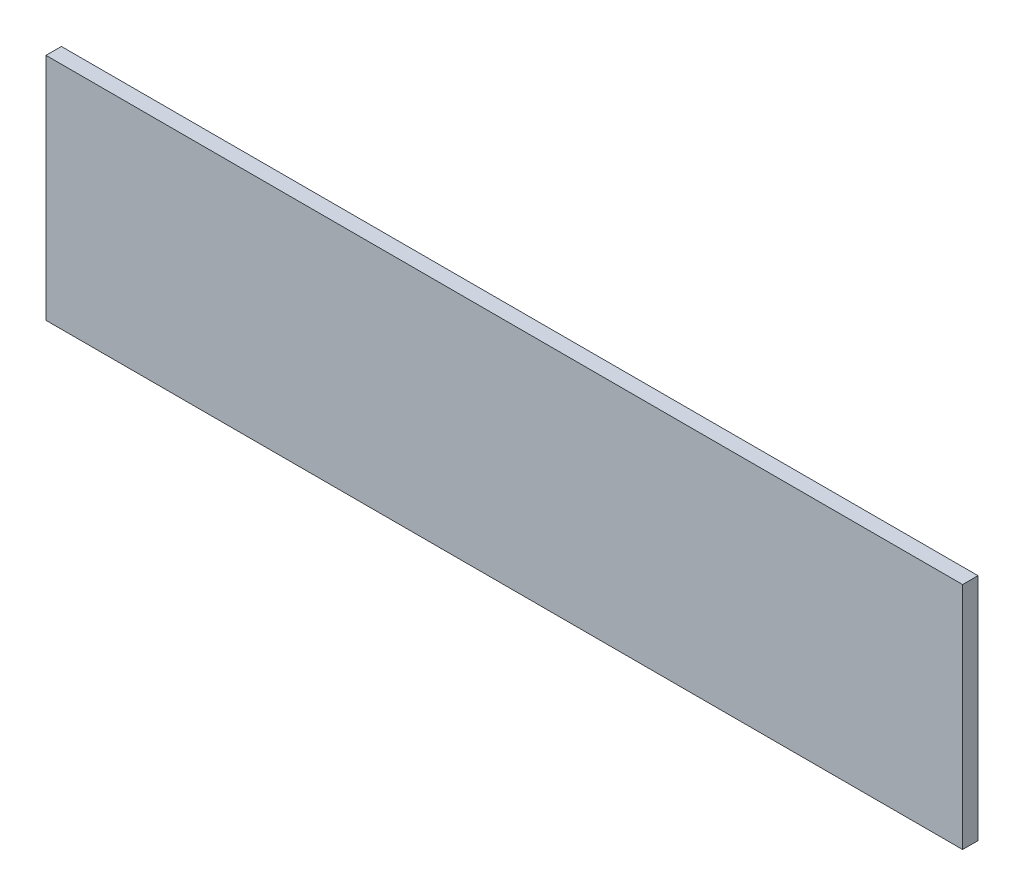
SolidWorks part; units mm, degrees
ref_plane "Front Plane" through (0, 0, 0) normal (0, 0, 1) x (1, 0, 0)
ref_plane "Top Plane" through (0, 0, 0) normal (0, 1, 0) x (1, 0, 0)
ref_plane "Right Plane" through (0, 0, 0) normal (1, 0, 0) x (0, 0, -1)
sketch "Sketch1" plane through (0, 0, 0) normal (0, 0, 1) x (1, 0, 0)
  line L1 (0, 0) -> (80.137, 0)
  line L2 (0, 0) -> (0, 20.066)
  line L3 (0, 20.066) -> (80.137, 20.066)
  line L4 (80.137, 0) -> (80.137, 20.066)
  dimension "D1" = 20.066
  dimension "D2" = 80.137
extrude "Boss-Extrude1" add sketch "Sketch1" along normal blind 1.3462
